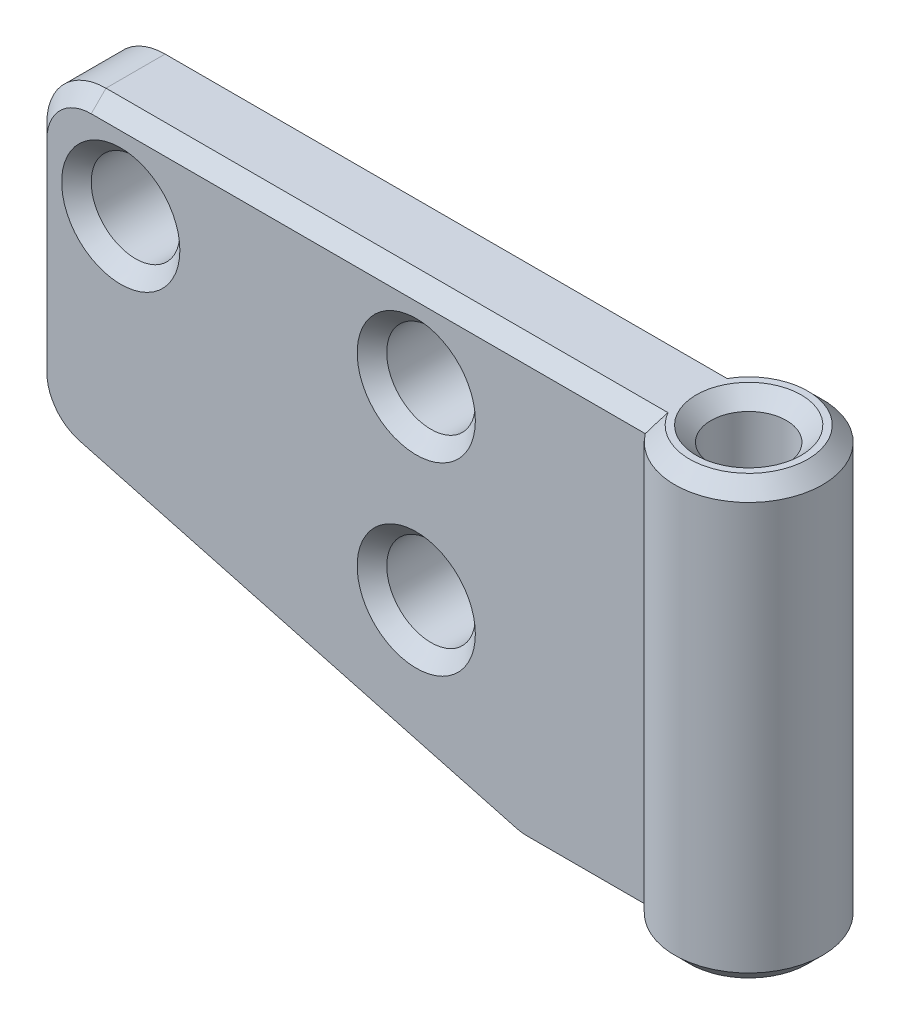
SolidWorks part; units mm, degrees
ref_plane "前视基准面" through (0, 0, 0) normal (0, 0, 1) x (1, 0, 0)
ref_plane "上视基准面" through (0, 0, 0) normal (0, 1, 0) x (1, 0, 0)
ref_plane "右视基准面" through (0, 0, 0) normal (1, 0, 0) x (0, 0, -1)
other "Configuration Table"
sketch "草图2" plane through (0, 0, 0) normal (0, 0, 1) x (1, 0, 0)
  line L0 (0, 0) -> (20, 0) construction
  line L1 (20, 0) -> (20, -12.5) construction
  line L2 (0, 0) -> (-6, 0) construction
  line L3 (-6, 0) -> (-6, 6) construction
  line L4 (20, -12.5) -> (20, -23.58) construction
  line L5 (20, -23.58) -> (27, -23.58) construction
  line L6 (27, -23.58) -> (39.5, -23.58) construction
  line L7 (26.4913, -23.4437) -> (-3.0353, -15.5321)
  line L8 (-2, 6) -> (39.5, 6)
  line L9 (-6, 6) -> (-6, -23.58) construction
  line L10 (-6, -23.58) -> (39.5, -23.58) construction
  line L11 (39.5, 6) -> (39.5, -23.58)
  line L12 (-6, -11.6684) -> (-6, 2)
  line L13 (27.5266, -23.58) -> (39.5, -23.58)
  circle A0 centre (0, 0) radius 3
  circle A1 centre (20, 0) radius 3
  circle A2 centre (20, -12.5) radius 3
  arc A3 (26.4913, -23.4437) -> (27.5266, -23.58) centre (27.5266, -19.58) ccw
  arc A4 (-3.0353, -15.5321) -> (-6, -11.6684) centre (-2, -11.6684) cw
  arc A5 (-2, 6) -> (-6, 2) centre (-2, 2) ccw
  point P20 (-6, -14.7377)
  dimension "D1" = 6
  dimension "D3" = 6
  dimension "D5" = 6
  dimension "D12" = 4
  dimension "D2" = 20
  dimension "D4" = 12.5
  dimension "D6" = 6
  dimension "D7" = 6
  dimension "D8" = 11.08
  dimension "D9" = 7
  dimension "D10" = 12.5
  dimension "D11" = 15
  dimension "D13" = 29.58
extrude "凸台-拉伸1" add sketch "草图2" along normal blind 6
sketch "草图3" plane through (0, 6, 0) normal (0, 1, 0) x (1, 0, 0)
  line L0 (39.5, -6) -> (39.5, 0) construction
  circle A0 centre (39.5, -3) radius 5
  dimension "D1" = 10
extrude "凸台-拉伸2" add sketch "草图3" against normal through all contours A0
sketch "草图4" plane through (0, 6, 0) normal (0, 1, 0) x (1, 0, 0)
  circle A0 centre (39.5, -3) radius 2.55
  dimension "D1" = 5.1
extrude "切除-拉伸1" cut sketch "草图4" against normal through all
chamfer "倒角1" distance 1 angle 45 23 edges at (27.0045, -23.5458, 6) (31.5133, -23.58, 6) (44.5, -23.58, 3) (31.5133, -23.58, 0) (27.0045, -23.5458, 0) (11.728, -19.4879, 6) (11.728, -19.4879, 0) (-5.1734, -14.1034, 6) (-5.1734, -14.1034, 0) (-6, -4.8342, 6) (-4.8284, 4.8284, 6) (-6, -4.8342, 0) (-4.8284, 4.8284, 0) (16.75, 6, 0) (16.75, 6, 6) (44.5, 6, 3) (39.5, 6, 5.55) (3, 0, 6) (23, -12.5, 6) (23, 0, 6) (3, 0, 0) (23, -12.5, 0) (23, 0, 0)
